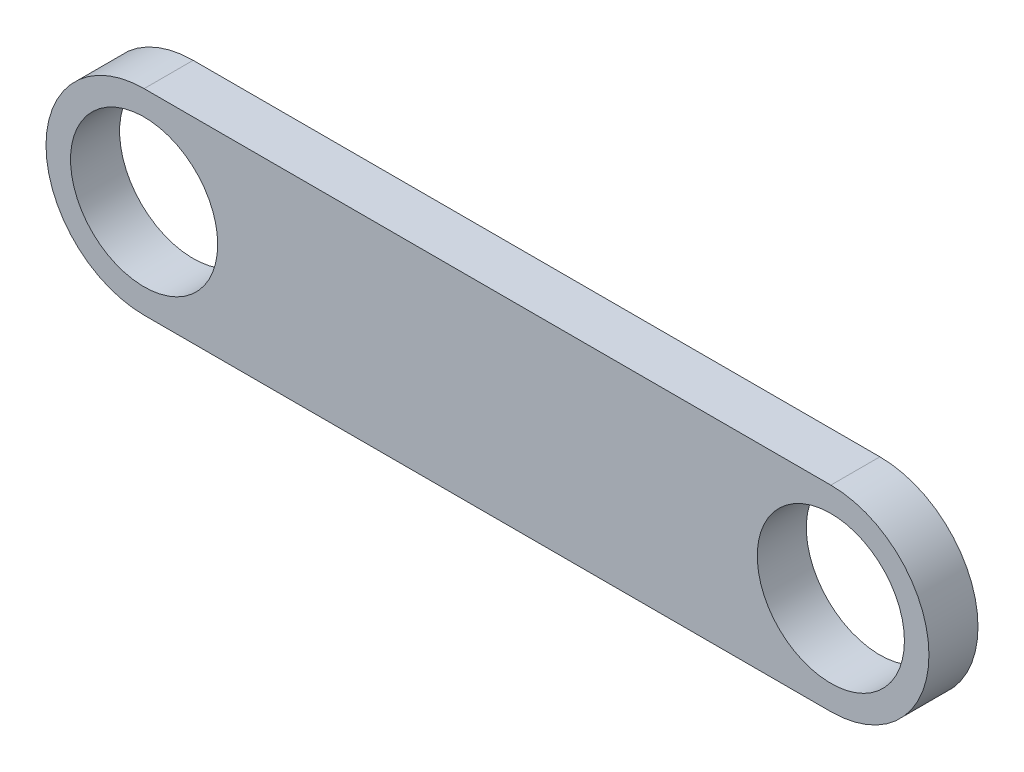
SolidWorks part; units mm, degrees
ref_plane "Спереди" through (0, 0, 0) normal (0, 0, 1) x (1, 0, 0)
ref_plane "Сверху" through (0, 0, 0) normal (0, 1, 0) x (1, 0, 0)
ref_plane "Справа" through (0, 0, 0) normal (1, 0, 0) x (0, 0, -1)
other "Configuration Table"
sketch "Эскиз1" plane through (0, 0, 0) normal (0, 0, 1) x (1, 0, 0)
  line L0 (0, 0) -> (140, 0) construction
  line L1 (0, 20) -> (140, 20)
  line L2 (0, -20) -> (140, -20)
  arc A0 (0, 20) -> (0, -20) centre (0, 0) ccw
  arc A1 (140, -20) -> (140, 20) centre (140, 0) ccw
  circle A2 centre (0, 0) radius 15
  circle A3 centre (140, 0) radius 15
  point P3 (70, 0)
  dimension "D1" = 140
  dimension "D3" = 30
  dimension "D4" = 30
  dimension "D2" = 40
extrude "Бобышка-Вытянуть2" add sketch "Эскиз1" along normal blind 10
